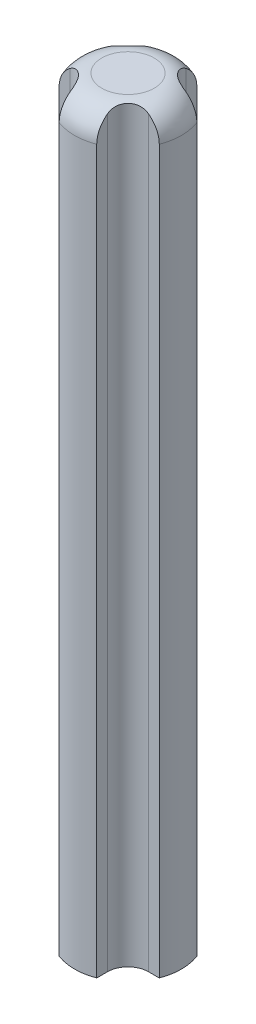
SolidWorks part; units mm, degrees
ref_plane "Front Plane" through (0, 0, 0) normal (0, 0, 1) x (1, 0, 0)
ref_plane "Top Plane" through (0, 0, 0) normal (0, 1, 0) x (1, 0, 0)
ref_plane "Right Plane" through (0, 0, 0) normal (1, 0, 0) x (0, 0, -1)
sketch "Sketch1" plane through (0, 0, 0) normal (0, 1, 0) x (1, 0, 0)
  circle A0 centre (0, 0) radius 3.925
  dimension "D1" = 7.85
extrude "Boss-Extrude1" add sketch "Sketch1" along normal blind 55
fillet "Fillet1" radius 2 1 edges at (0, 55, 3.925)
sketch "Sketch2" plane through (0, 55, 0) normal (0, 1, 0) x (1, 0, 0)
  line L0 (0, 0) -> (1.3789, -1.3789) construction
  line L1 (1.3789, -1.3789) -> (0, -1.3789) construction
  line L2 (1.3789, -1.3789) -> (3.8789, -1.3789)
  line L3 (1.3789, -1.3789) -> (1.3789, -3.8789)
  line L4 (1.3789, -3.8789) -> (3.8789, -3.8789)
  line L5 (3.8789, -1.3789) -> (3.8789, -3.8789)
  line L6 (0, -1.3789) -> (0, 0) construction
  dimension "D1" = 1.95
  dimension "D2" = 2.5
extrude "Cut-Extrude1" cut sketch "Sketch2" against normal through all
pattern_circular "CirPattern1" count 4 over 360 about axis through (0, 0, 0) along (0, 1, 0) of "Cut-Extrude1"
fillet "Fillet2" radius 1.5 4 edges at (1.3789, 27.4999, -1.3789) (-1.3789, 27.4999, -1.3789) (-1.3789, 27.4999, 1.3789) (1.3789, 27.4999, 1.3789)
